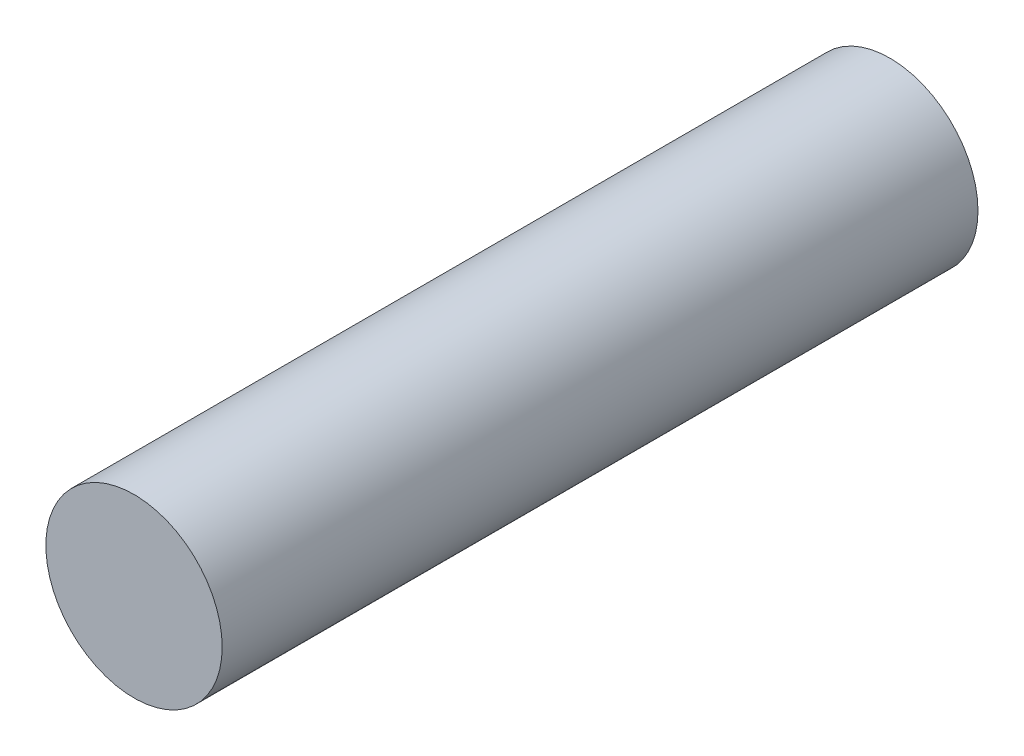
SolidWorks part; units mm, degrees
ref_plane "Front Plane" through (0, 0, 0) normal (0, 0, 1) x (1, 0, 0)
ref_plane "Top Plane" through (0, 0, 0) normal (0, 1, 0) x (1, 0, 0)
ref_plane "Right Plane" through (0, 0, 0) normal (1, 0, 0) x (0, 0, -1)
sketch "Sketch1" plane through (0, 0, 0) normal (0, 0, 1) x (1, 0, 0)
  circle A0 centre (-186.6572, -243) radius 7
  dimension "D1" = 14
extrude "Boss-Extrude1" add sketch "Sketch1" along normal blind 60
